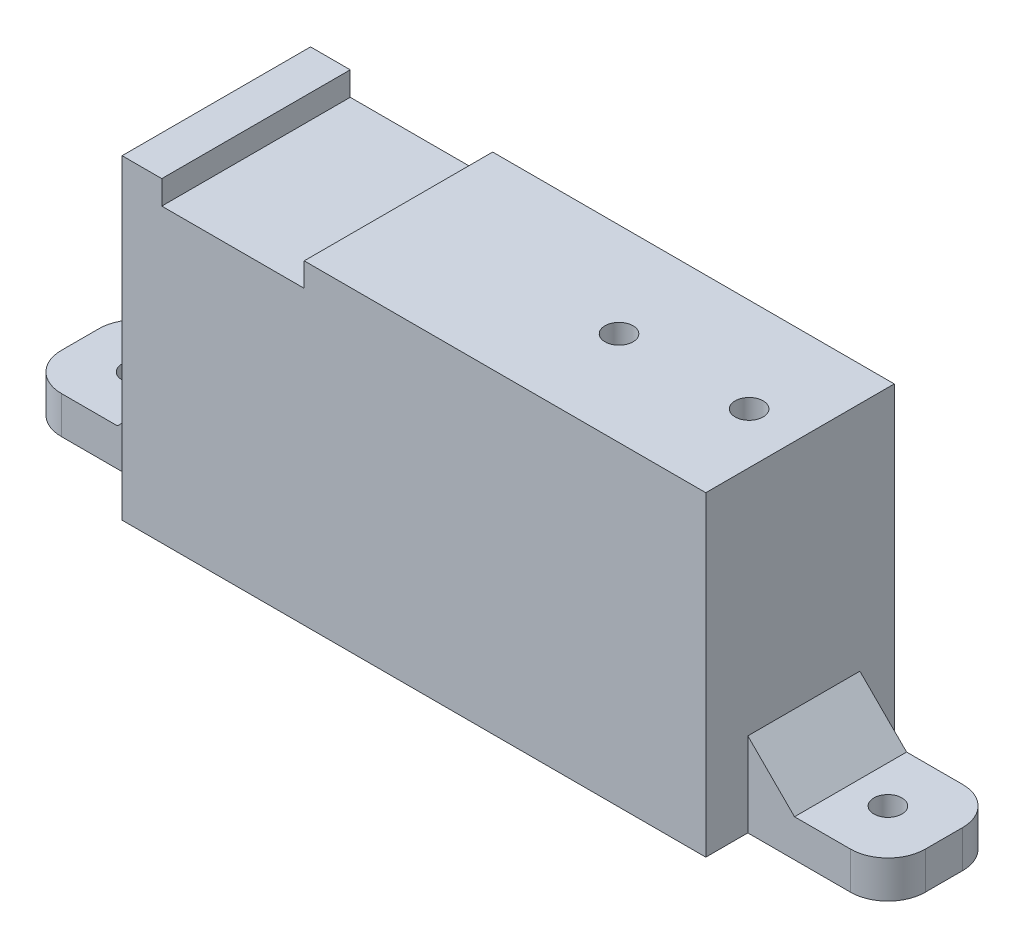
SolidWorks part; units mm, degrees
ref_plane "Спереди" through (0, 0, 0) normal (0, 0, 1) x (1, 0, 0)
ref_plane "Сверху" through (0, 0, 0) normal (0, 1, 0) x (1, 0, 0)
ref_plane "Справа" through (0, 0, 0) normal (1, 0, 0) x (0, 0, -1)
other "Configuration Table"
sketch "основание" plane through (0, 0, 0) normal (0, 1, 0) x (1, 0, 0)
  line L1 (-31.25, -10.09) -> (31.25, -10.09)
  line L2 (-31.25, -10.09) -> (-31.25, 10.09)
  line L3 (-31.25, 10.09) -> (31.25, 10.09)
  line L4 (31.25, -10.09) -> (31.25, 10.09)
  line L5 (-31.25, -10.09) -> (31.25, 10.09) construction
  line L6 (-31.25, 10.09) -> (31.25, -10.09) construction
  point P0 (0, 0)
  dimension "D1" = 20.18
  dimension "D2" = 62.5
extrude "Бобышка-Вытянуть1" add sketch "основание" along normal blind 33.8
sketch "Эскиз6" plane through (0, 33.8, 0) normal (0, 1, 0) x (1, 0, 0)
  line L0 (31.25, 10.09) -> (-31.25, 10.09) construction
  line L1 (-27, 10.09) -> (-11.75, 10.09)
  line L2 (-27, 10.09) -> (-27, -10.09)
  line L3 (-27, -10.09) -> (-11.75, -10.09)
  line L4 (-11.75, 10.09) -> (-11.75, -10.09)
  line L5 (-31.25, -10.09) -> (31.25, -10.09) construction
  dimension "D1" = 15.25
  dimension "D2" = 4.25
extrude "Вырез-Вытянуть1" cut sketch "Эскиз6" against normal blind 2.55
sketch "Эскиз7" plane through (0, 33.8, 0) normal (0, 1, 0) x (1, 0, 0)
  line L0 (0, 0) -> (46.5539, 0) construction
  line L2 (31.25, -10.09) -> (31.25, 10.09) construction
  circle A0 centre (25.8, 0) radius 1.5
  circle A1 centre (11.87, 0) radius 1.5
  point P7 (27.3, 0)
  point P10 (13.37, 0)
  point P11 (24.3, 0)
  dimension "D1" = 3
  dimension "D2" = 3
  dimension "D3" = 3.95
  dimension "D4" = 10.93
extrude "Вырез-Вытянуть2" cut sketch "Эскиз7" against normal blind 15 contours L0 A0 | A0 L0 | A1
sketch "Эскиз8" plane through (0, 0, 0) normal (0, -1, 0) x (1, 0, 0)
  line L0 (-31.25, -10.09) -> (-31.25, 10.09) construction
  line L1 (-31.25, 5.59) -> (-42.25, 5.59)
  line L2 (-31.25, 5.59) -> (-31.25, -6.41)
  line L3 (-31.25, -6.41) -> (-42.25, -6.41)
  line L4 (-46.25, 1.59) -> (-46.25, -2.41)
  line L5 (-31.25, 10.09) -> (31.25, 10.09) construction
  line L6 (0, 0) -> (0, 20.7226) construction
  line L7 (31.25, -6.41) -> (42.25, -6.41)
  line L8 (46.25, 1.59) -> (46.25, -2.41)
  line L9 (31.25, 5.59) -> (42.25, 5.59)
  line L10 (31.25, 5.59) -> (31.25, -6.41)
  circle A0 centre (-40.25, -0.41) radius 1.5
  circle A1 centre (40.25, -0.41) radius 1.5
  arc A2 (-46.25, -2.41) -> (-42.25, -6.41) centre (-42.25, -2.41) ccw
  arc A3 (-46.25, 1.59) -> (-42.25, 5.59) centre (-42.25, 1.59) cw
  arc A4 (42.25, -6.41) -> (46.25, -2.41) centre (42.25, -2.41) ccw
  arc A5 (46.25, 1.59) -> (42.25, 5.59) centre (42.25, 1.59) ccw
  point P21 (-46.25, -6.41)
  point P24 (-46.25, 5.59)
  point P27 (46.25, -6.41)
  point P30 (46.25, 5.59)
  dimension "D4" = 3
  dimension "D7" = 4
  dimension "D1" = 15
  dimension "D2" = 12
  dimension "D3" = 4.5
  dimension "D5" = 6
  dimension "D6" = 6
extrude "Бобышка-Вытянуть2" add sketch "Эскиз8" against normal blind 4
chamfer "Фаска1" distance 5 angle 45 1 edges at (-31.25, 4, -0.41)
chamfer "Фаска2" distance 5 angle 45 1 edges at (31.25, 4, -0.41)
